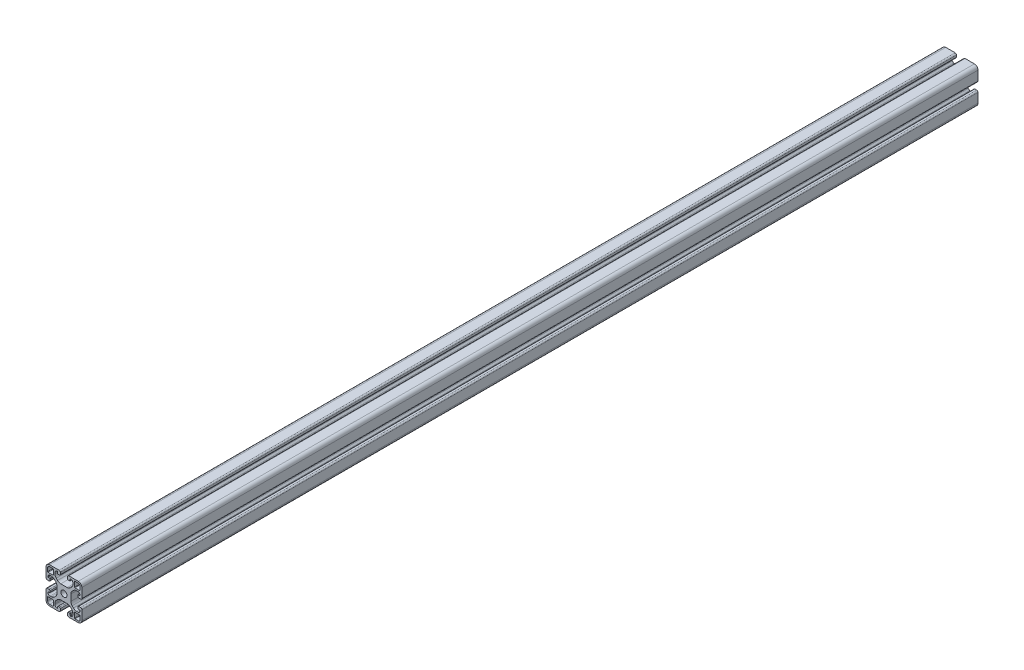
SolidWorks part; units mm, degrees
ref_plane "Front" through (0, 0, 0) normal (0, 0, 1) x (1, 0, 0)
ref_plane "Top" through (0, 0, 0) normal (0, 1, 0) x (1, 0, 0)
ref_plane "Right" through (0, 0, 0) normal (1, 0, 0) x (0, 0, -1)
sketch "Sketch1" plane through (0, 0, 0) normal (0, 0, 1) x (1, 0, 0)
  line L0 (226.845, 367.6546) -> (226.845, 357.1546)
  line L1 (228.345, 355.6546) -> (230.345, 355.6546)
  line L2 (231.345, 356.6546) -> (231.345, 358.1546)
  line L3 (230.845, 358.6546) -> (229.345, 358.6546)
  line L4 (231.345, 361.6546) -> (232.6526, 361.6546)
  line L5 (236.1881, 360.1902) -> (237.6305, 358.7478)
  line L6 (239.095, 355.2122) -> (239.095, 351.6546)
  line L7 (239.095, 351.6546) -> (239.095, 348.097)
  line L8 (237.6305, 344.5615) -> (236.1881, 343.1191)
  line L9 (232.6526, 341.6546) -> (231.345, 341.6546)
  line L10 (229.345, 344.6546) -> (230.845, 344.6546)
  line L11 (231.345, 345.1546) -> (231.345, 346.6546)
  line L12 (230.345, 347.6546) -> (228.345, 347.6546)
  line L13 (226.845, 346.1546) -> (226.845, 335.6546)
  line L14 (230.845, 331.6546) -> (241.345, 331.6546)
  line L15 (242.845, 333.1546) -> (242.845, 335.1546)
  line L16 (241.845, 336.1546) -> (240.345, 336.1546)
  line L17 (239.845, 335.6546) -> (239.845, 334.1546)
  line L18 (236.845, 336.1546) -> (236.845, 337.4622)
  line L19 (238.3095, 340.9978) -> (239.7518, 342.4402)
  line L20 (243.2874, 343.9046) -> (246.845, 343.9046)
  line L21 (246.845, 343.9046) -> (250.4026, 343.9046)
  line L22 (253.9381, 342.4402) -> (255.3805, 340.9978)
  line L23 (256.845, 337.4622) -> (256.845, 336.1546)
  line L24 (253.845, 334.1546) -> (253.845, 335.6546)
  line L25 (253.345, 336.1546) -> (251.845, 336.1546)
  line L26 (250.845, 335.1546) -> (250.845, 333.1546)
  line L27 (252.345, 331.6546) -> (262.845, 331.6546)
  line L28 (266.845, 335.6546) -> (266.845, 346.1546)
  line L29 (265.345, 347.6546) -> (263.345, 347.6546)
  line L30 (262.345, 346.6546) -> (262.345, 345.1546)
  line L31 (262.845, 344.6546) -> (264.345, 344.6546)
  line L32 (262.345, 341.6546) -> (261.0374, 341.6546)
  line L33 (257.5018, 343.1191) -> (256.0595, 344.5615)
  line L34 (254.595, 348.097) -> (254.595, 351.6546)
  line L35 (254.595, 351.6546) -> (254.595, 355.2122)
  line L36 (256.0595, 358.7478) -> (257.5018, 360.1902)
  line L37 (261.0374, 361.6546) -> (262.345, 361.6546)
  line L38 (264.345, 358.6546) -> (262.845, 358.6546)
  line L39 (262.345, 358.1546) -> (262.345, 356.6546)
  line L40 (263.345, 355.6546) -> (265.345, 355.6546)
  line L41 (266.845, 357.1546) -> (266.845, 367.6546)
  line L42 (262.845, 371.6546) -> (252.345, 371.6546)
  line L43 (250.845, 370.1546) -> (250.845, 368.1546)
  line L44 (251.845, 367.1546) -> (253.345, 367.1546)
  line L45 (253.845, 367.6546) -> (253.845, 369.1546)
  line L46 (256.845, 367.1546) -> (256.845, 365.847)
  line L47 (255.3805, 362.3115) -> (253.9381, 360.8691)
  line L48 (250.4026, 359.4046) -> (246.845, 359.4046)
  line L49 (246.845, 359.4046) -> (243.2874, 359.4046)
  line L50 (239.7518, 360.8691) -> (238.3095, 362.3115)
  line L51 (236.845, 365.847) -> (236.845, 367.1546)
  line L52 (239.845, 369.1546) -> (239.845, 367.6546)
  line L53 (240.345, 367.1546) -> (241.845, 367.1546)
  line L54 (242.845, 368.1546) -> (242.845, 370.1546)
  line L55 (241.345, 371.6546) -> (230.845, 371.6546)
  line L56 (235.045, 333.9546) -> (235.045, 339.3546)
  line L57 (234.545, 339.8546) -> (229.145, 339.8546)
  line L58 (228.645, 339.3546) -> (228.645, 335.6546)
  line L59 (230.845, 333.4546) -> (234.545, 333.4546)
  line L60 (229.145, 363.4546) -> (234.545, 363.4546)
  line L61 (235.045, 363.9546) -> (235.045, 369.3546)
  line L62 (234.545, 369.8546) -> (230.845, 369.8546)
  line L63 (228.645, 367.6546) -> (228.645, 363.9546)
  line L64 (264.545, 339.8546) -> (259.145, 339.8546)
  line L65 (258.645, 339.3546) -> (258.645, 333.9546)
  line L66 (259.145, 333.4546) -> (262.845, 333.4546)
  line L67 (265.045, 335.6546) -> (265.045, 339.3546)
  line L68 (258.645, 369.3546) -> (258.645, 363.9546)
  line L69 (259.145, 363.4546) -> (264.545, 363.4546)
  line L70 (265.045, 363.9546) -> (265.045, 367.6546)
  line L71 (262.845, 369.8546) -> (259.145, 369.8546)
  circle A0 centre (246.845, 351.6546) radius 3.4
  arc A1 (226.845, 357.1546) -> (228.345, 355.6546) centre (228.345, 357.1546) ccw
  arc A2 (230.345, 355.6546) -> (231.345, 356.6546) centre (230.345, 356.6546) ccw
  arc A3 (231.345, 358.1546) -> (230.845, 358.6546) centre (230.845, 358.1546) ccw
  arc A4 (229.345, 358.6546) -> (228.845, 359.1546) centre (229.345, 359.1546) cw
  arc A5 (228.845, 359.1546) -> (231.345, 361.6546) centre (231.345, 359.1546) cw
  arc A6 (232.6526, 361.6546) -> (236.1881, 360.1902) centre (232.6526, 356.6546) cw
  arc A7 (237.6305, 358.7478) -> (239.095, 355.2122) centre (234.095, 355.2122) cw
  arc A8 (239.095, 348.097) -> (237.6305, 344.5615) centre (234.095, 348.097) cw
  arc A9 (236.1881, 343.1191) -> (232.6526, 341.6546) centre (232.6526, 346.6546) cw
  arc A10 (231.345, 341.6546) -> (228.845, 344.1546) centre (231.345, 344.1546) cw
  arc A11 (228.845, 344.1546) -> (229.345, 344.6546) centre (229.345, 344.1546) cw
  arc A12 (230.845, 344.6546) -> (231.345, 345.1546) centre (230.845, 345.1546) ccw
  arc A13 (231.345, 346.6546) -> (230.345, 347.6546) centre (230.345, 346.6546) ccw
  arc A14 (228.345, 347.6546) -> (226.845, 346.1546) centre (228.345, 346.1546) ccw
  arc A15 (226.845, 335.6546) -> (230.845, 331.6546) centre (230.845, 335.6546) ccw
  arc A16 (241.345, 331.6546) -> (242.845, 333.1546) centre (241.345, 333.1546) ccw
  arc A17 (242.845, 335.1546) -> (241.845, 336.1546) centre (241.845, 335.1546) ccw
  arc A18 (240.345, 336.1546) -> (239.845, 335.6546) centre (240.345, 335.6546) ccw
  arc A19 (239.845, 334.1546) -> (239.345, 333.6546) centre (239.345, 334.1546) cw
  arc A20 (239.345, 333.6546) -> (236.845, 336.1546) centre (239.345, 336.1546) cw
  arc A21 (236.845, 337.4622) -> (238.3095, 340.9978) centre (241.845, 337.4622) cw
  arc A22 (239.7518, 342.4402) -> (243.2874, 343.9046) centre (243.2874, 338.9046) cw
  arc A23 (250.4026, 343.9046) -> (253.9381, 342.4402) centre (250.4026, 338.9046) cw
  arc A24 (255.3805, 340.9978) -> (256.845, 337.4622) centre (251.845, 337.4622) cw
  arc A25 (256.845, 336.1546) -> (254.345, 333.6546) centre (254.345, 336.1546) cw
  arc A26 (254.345, 333.6546) -> (253.845, 334.1546) centre (254.345, 334.1546) cw
  arc A27 (253.845, 335.6546) -> (253.345, 336.1546) centre (253.345, 335.6546) ccw
  arc A28 (251.845, 336.1546) -> (250.845, 335.1546) centre (251.845, 335.1546) ccw
  arc A29 (250.845, 333.1546) -> (252.345, 331.6546) centre (252.345, 333.1546) ccw
  arc A30 (262.845, 331.6546) -> (266.845, 335.6546) centre (262.845, 335.6546) ccw
  arc A31 (266.845, 346.1546) -> (265.345, 347.6546) centre (265.345, 346.1546) ccw
  arc A32 (263.345, 347.6546) -> (262.345, 346.6546) centre (263.345, 346.6546) ccw
  arc A33 (262.345, 345.1546) -> (262.845, 344.6546) centre (262.845, 345.1546) ccw
  arc A34 (264.345, 344.6546) -> (264.845, 344.1546) centre (264.345, 344.1546) cw
  arc A35 (264.845, 344.1546) -> (262.345, 341.6546) centre (262.345, 344.1546) cw
  arc A36 (261.0374, 341.6546) -> (257.5018, 343.1191) centre (261.0374, 346.6546) cw
  arc A37 (256.0595, 344.5615) -> (254.595, 348.097) centre (259.595, 348.097) cw
  arc A38 (254.595, 355.2122) -> (256.0595, 358.7478) centre (259.595, 355.2122) cw
  arc A39 (257.5018, 360.1902) -> (261.0374, 361.6546) centre (261.0374, 356.6546) cw
  arc A40 (262.345, 361.6546) -> (264.845, 359.1546) centre (262.345, 359.1546) cw
  arc A41 (264.845, 359.1546) -> (264.345, 358.6546) centre (264.345, 359.1546) cw
  arc A42 (262.845, 358.6546) -> (262.345, 358.1546) centre (262.845, 358.1546) ccw
  arc A43 (262.345, 356.6546) -> (263.345, 355.6546) centre (263.345, 356.6546) ccw
  arc A44 (265.345, 355.6546) -> (266.845, 357.1546) centre (265.345, 357.1546) ccw
  arc A45 (266.845, 367.6546) -> (262.845, 371.6546) centre (262.845, 367.6546) ccw
  arc A46 (252.345, 371.6546) -> (250.845, 370.1546) centre (252.345, 370.1546) ccw
  arc A47 (250.845, 368.1546) -> (251.845, 367.1546) centre (251.845, 368.1546) ccw
  arc A48 (253.345, 367.1546) -> (253.845, 367.6546) centre (253.345, 367.6546) ccw
  arc A49 (253.845, 369.1546) -> (254.345, 369.6546) centre (254.345, 369.1546) cw
  arc A50 (254.345, 369.6546) -> (256.845, 367.1546) centre (254.345, 367.1546) cw
  arc A51 (256.845, 365.847) -> (255.3805, 362.3115) centre (251.845, 365.847) cw
  arc A52 (253.9381, 360.8691) -> (250.4026, 359.4046) centre (250.4026, 364.4046) cw
  arc A53 (243.2874, 359.4046) -> (239.7518, 360.8691) centre (243.2874, 364.4046) cw
  arc A54 (238.3095, 362.3115) -> (236.845, 365.847) centre (241.845, 365.847) cw
  arc A55 (236.845, 367.1546) -> (239.345, 369.6546) centre (239.345, 367.1546) cw
  arc A56 (239.345, 369.6546) -> (239.845, 369.1546) centre (239.345, 369.1546) cw
  arc A57 (239.845, 367.6546) -> (240.345, 367.1546) centre (240.345, 367.6546) ccw
  arc A58 (241.845, 367.1546) -> (242.845, 368.1546) centre (241.845, 368.1546) ccw
  arc A59 (242.845, 370.1546) -> (241.345, 371.6546) centre (241.345, 370.1546) ccw
  arc A60 (230.845, 371.6546) -> (226.845, 367.6546) centre (230.845, 367.6546) ccw
  arc A61 (235.045, 339.3546) -> (234.545, 339.8546) centre (234.545, 339.3546) ccw
  arc A62 (229.145, 339.8546) -> (228.645, 339.3546) centre (229.145, 339.3546) ccw
  arc A63 (228.645, 335.6546) -> (230.845, 333.4546) centre (230.845, 335.6546) ccw
  arc A64 (234.545, 333.4546) -> (235.045, 333.9546) centre (234.545, 333.9546) ccw
  arc A65 (228.645, 363.9546) -> (229.145, 363.4546) centre (229.145, 363.9546) ccw
  arc A66 (234.545, 363.4546) -> (235.045, 363.9546) centre (234.545, 363.9546) ccw
  arc A67 (235.045, 369.3546) -> (234.545, 369.8546) centre (234.545, 369.3546) ccw
  arc A68 (230.845, 369.8546) -> (228.645, 367.6546) centre (230.845, 367.6546) ccw
  arc A69 (265.045, 339.3546) -> (264.545, 339.8546) centre (264.545, 339.3546) ccw
  arc A70 (259.145, 339.8546) -> (258.645, 339.3546) centre (259.145, 339.3546) ccw
  arc A71 (258.645, 333.9546) -> (259.145, 333.4546) centre (259.145, 333.9546) ccw
  arc A72 (262.845, 333.4546) -> (265.045, 335.6546) centre (262.845, 335.6546) ccw
  arc A73 (258.645, 363.9546) -> (259.145, 363.4546) centre (259.145, 363.9546) ccw
  arc A74 (264.545, 363.4546) -> (265.045, 363.9546) centre (264.545, 363.9546) ccw
  arc A75 (265.045, 367.6546) -> (262.845, 369.8546) centre (262.845, 367.6546) ccw
  arc A76 (259.145, 369.8546) -> (258.645, 369.3546) centre (259.145, 369.3546) ccw
  point P189 (226.845, 331.6546)
  point P190 (226.845, 351.6546)
  point P191 (231.345, 351.6546)
  point P192 (246.845, 331.6546)
  point P193 (246.845, 336.1546)
  point P205 (231.302, 356.3646)
  point P206 (231.302, 356.3646)
  point P207 (226.845, 371.6546)
  point P208 (246.845, 367.1546)
  point P209 (246.845, 371.6546)
  point P221 (266.845, 331.6546)
  point P222 (262.345, 351.6546)
  point P223 (266.845, 351.6546)
  point P235 (266.845, 371.6546)
extrude "Base-Extrude" add sketch "Sketch1" along normal blind 1000
